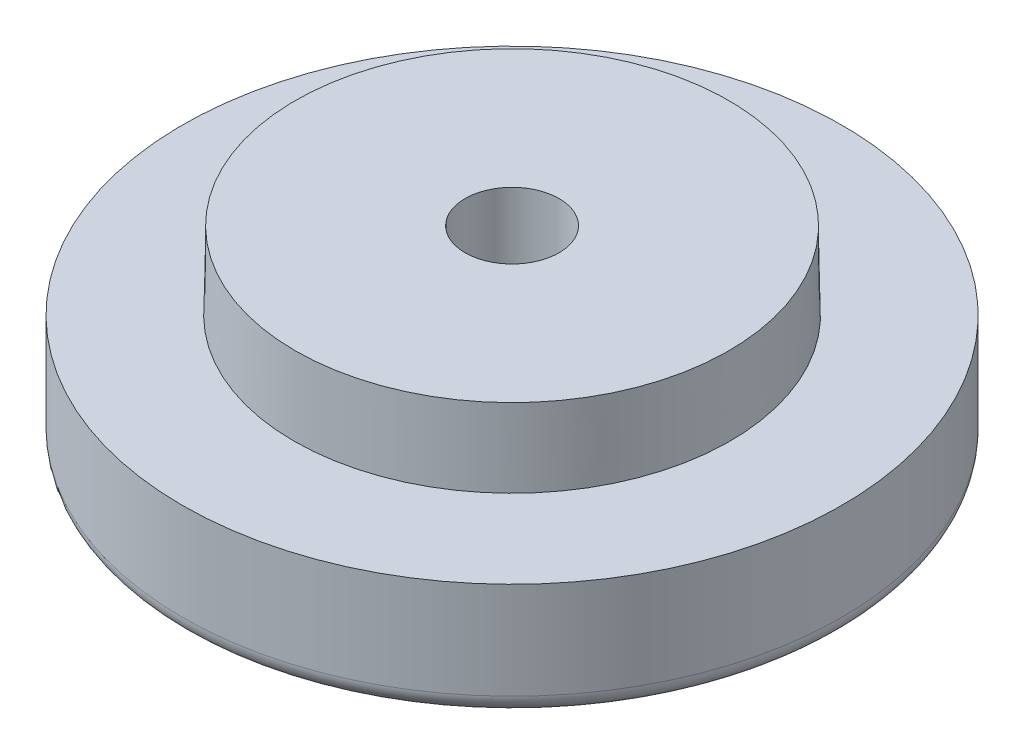
SolidWorks part; units mm, degrees
ref_plane "Front Plane" through (0, 0, 0) normal (0, 0, 1) x (1, 0, 0)
ref_plane "Top Plane" through (0, 0, 0) normal (0, 1, 0) x (1, 0, 0)
ref_plane "Right Plane" through (0, 0, 0) normal (1, 0, 0) x (0, 0, -1)
sketch "Sketch2" plane through (0, 0, 0) normal (0, 1, 0) x (1, 0, 0)
  circle A0 centre (0, 0) radius 34
  dimension "D1" = 68
extrude "Boss-Extrude1" add sketch "Sketch2" along normal blind 12
sketch "Sketch3" plane through (0, 12, 0) normal (0, 1, 0) x (1, 0, 0)
  circle A0 centre (0, 0) radius 22.5
  dimension "D1" = 45
extrude "Boss-Extrude3" add sketch "Sketch3" along normal blind 8 draft 1 separate body contours A0
sketch "Sketch4" plane through (0, 20, 0) normal (0, 1, 0) x (1, 0, 0)
  circle A0 centre (0, 0) radius 4.85
  dimension "D1" = 9.7
extrude "Cut-Extrude1" cut sketch "Sketch4" against normal through all
fillet "Fillet1" radius 2 1 edges at (0, 0, 34)
